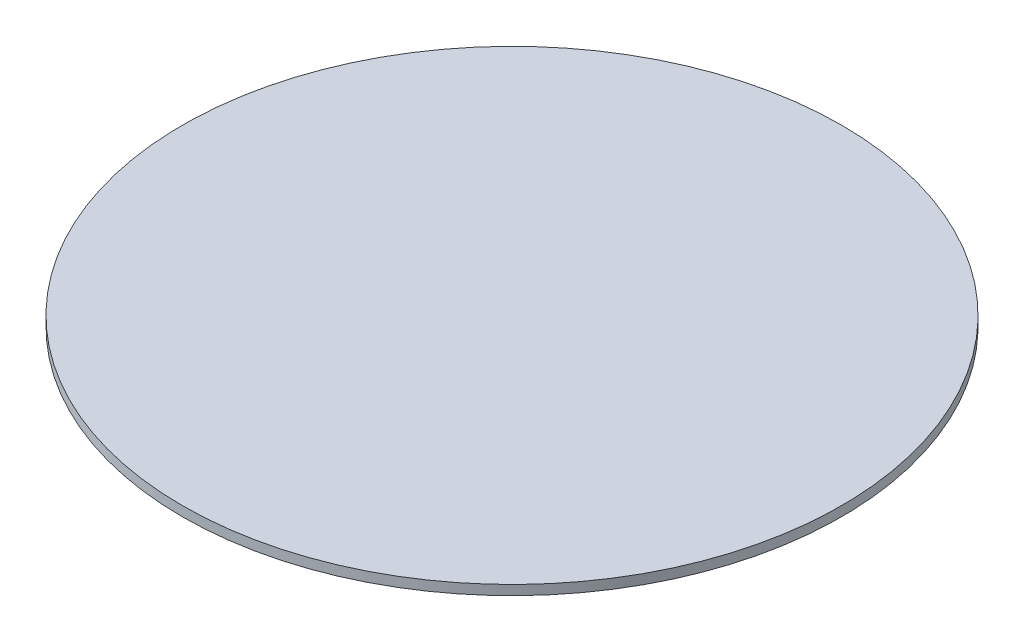
SolidWorks part; units mm, degrees
ref_plane "前视基准面" through (0, 0, 0) normal (0, 0, 1) x (1, 0, 0)
ref_plane "上视基准面" through (0, 0, 0) normal (0, 1, 0) x (1, 0, 0)
ref_plane "右视基准面" through (0, 0, 0) normal (1, 0, 0) x (0, 0, -1)
sketch "草图1" plane through (0, 0, 0) normal (0, 1, 0) x (1, 0, 0)
  circle A0 centre (0, 0) radius 170
  dimension "D1" = 340
extrude "凸台-拉伸1" add sketch "草图1" along normal blind 5
sketch "草图7" plane through (0, 0, 0) normal (0, -1, 0) x (1, 0, 0)
  line L0 (-7, 0) -> (7, 0)
  line L1 (-7, 0) -> (-7, -12)
  line L2 (7, 0) -> (7, 12)
  line L3 (-7, 20.5) -> (-7, -44.5)
  line L4 (7, 44.5) -> (7, -20.5)
  line L6 (-7, 20.5) -> (-72, 20.5)
  line L7 (-7, 20.5) -> (-7, -44.5)
  line L8 (-7, -44.5) -> (-72, -44.5)
  line L9 (-72, 20.5) -> (-72, -44.5)
  line L10 (7, 44.5) -> (72, 44.5)
  line L11 (7, 44.5) -> (7, -20.5)
  line L12 (7, -20.5) -> (72, -20.5)
  line L13 (72, 44.5) -> (72, -20.5)
  circle A0 centre (-72, 20.5) radius 2
  circle A1 centre (-7, 20.5) radius 2
  circle A2 centre (-72, -44.5) radius 2
  circle A3 centre (-7, -44.5) radius 2
  circle A4 centre (7, -20.5) radius 2
  circle A5 centre (72, -20.5) radius 2
  circle A6 centre (7, 44.5) radius 2
  circle A7 centre (72, 44.5) radius 2
  point P4 (0, 0)
  point P9 (-7, -12)
  point P12 (7, 12)
  dimension "D8" = 4
  dimension "D9" = 4
  dimension "D10" = 4
  dimension "D11" = 4
  dimension "D12" = 4
  dimension "D13" = 4
  dimension "D14" = 4
  dimension "D15" = 4
  dimension "D1" = 14
  dimension "D2" = 12
  dimension "D3" = 12
  dimension "D4" = 65
  dimension "D5" = 65
  dimension "D6" = 65
  dimension "D7" = 65
extrude "切除-拉伸3" cut sketch "草图7" against normal blind 3 contours A0 | A2 | A3 | A1 | A4 | A5 | A7 | A6
sketch "草图8" plane through (0, 0, 0) normal (0, -1, 0) x (-1, 0, 0)
  line L0 (-170, 0) -> (170, 0)
  line L1 (0, 170) -> (0, -170)
  circle A0 centre (0, 0) radius 170 construction
  point P7 (0, 0)
  point P10 (0, 0)
sketch "草图9" plane through (0, 0, 0) normal (0, -1, 0) x (1, 0, 0)
  line L0 (-7, 0) -> (7, 0)
  line L1 (-7, 0) -> (-7, 10)
  line L2 (7, 0) -> (7, -10)
  line L3 (7, -32.5) -> (7, 32.5)
  line L4 (-7, 32.5) -> (-7, -32.5)
  line L6 (-7, 32.5) -> (-72, 32.5)
  line L7 (-7, 32.5) -> (-7, -32.5)
  line L8 (-7, -32.5) -> (-72, -32.5)
  line L9 (-72, 32.5) -> (-72, -32.5)
  line L10 (7, 32.5) -> (72, 32.5)
  line L11 (7, 32.5) -> (7, -32.5)
  line L12 (7, -32.5) -> (72, -32.5)
  line L13 (72, 32.5) -> (72, -32.5)
  circle A0 centre (-72, 32.5) radius 2
  circle A1 centre (-72, -32.5) radius 2
  circle A2 centre (72, 32.5) radius 2
  circle A3 centre (72, -32.5) radius 2
  circle A4 centre (-7, 32.5) radius 2
  circle A5 centre (7, 32.5) radius 2
  circle A6 centre (7, -32.5) radius 2
  circle A7 centre (-7, -32.5) radius 2
  point P4 (0, 0)
  point P13 (7, 0)
  point P16 (-7, 0)
  dimension "D2" = 65
  dimension "D3" = 65
  dimension "D5" = 4
  dimension "D7" = 4
  dimension "D10" = 4
  dimension "D11" = 4
  dimension "D12" = 4
  dimension "D13" = 4
  dimension "D4" = 4
  dimension "D6" = 4
  dimension "D1" = 14
  dimension "D8" = 65
  dimension "D9" = 65
extrude "切除-拉伸4" cut sketch "草图9" against normal blind 3 contours A0 | A1 | A4 | A7 | A6 | A5 | A2 | A3
sketch "草图11" plane through (0, 0, 0) normal (0, -1, 0) x (1, 0, 0)
  line L0 (-72, -44.5) -> (-72, -56.5)
  line L1 (-7, -44.5) -> (-7, -56.5)
  line L2 (-72, 20.5) -> (-72, 8.5)
  line L3 (-7, 20.5) -> (-7, 8.5)
  line L4 (7, 32.5) -> (7, 20.5)
  line L5 (7, 20.5) -> (7, 8.5)
  line L6 (72, 32.5) -> (72, 20.5)
  line L7 (72, 20.5) -> (72, 8.5)
  line L8 (7, -32.5) -> (7, -44.5)
  line L9 (7, -44.5) -> (7, -56.5)
  line L10 (-7, 32.5) -> (-7, 44.5)
  line L11 (-7, -32.5) -> (-7, -20.5)
  line L12 (-72, 44.5) -> (-72, 56.5)
  line L13 (-72, -20.5) -> (-72, -8.5)
  line L14 (-72, 8.5) -> (-72, -3.5)
  circle A0 centre (-72, 8.5) radius 2
  circle A1 centre (-7, 8.5) radius 2
  circle A2 centre (-72, -56.5) radius 2
  circle A3 centre (-7, -56.5) radius 2
  circle A4 centre (7, 8.5) radius 2
  circle A5 centre (7, 20.5) radius 2
  circle A6 centre (72, 20.5) radius 2
  circle A7 centre (72, 8.5) radius 2
  circle A8 centre (72, -44.5) radius 2
  circle A9 centre (72, -56.5) radius 2
  circle A10 centre (-72, 44.5) radius 2
  circle A11 centre (-7, 44.5) radius 2
  circle A12 centre (7, -44.5) radius 2
  circle A13 centre (7, -56.5) radius 2
  circle A14 centre (-7, -20.5) radius 2
  circle A15 centre (-72, -20.5) radius 2
  circle A16 centre (-72, 56.5) radius 2
  circle A17 centre (-7, 56.5) radius 2
  circle A18 centre (7, 56.5) radius 2
  circle A19 centre (72, 56.5) radius 2
  circle A21 centre (-72, -8.5) radius 2
  circle A22 centre (-7, -8.5) radius 2
  circle A24 centre (7, -8.5) radius 2
  circle A26 centre (72, -8.5) radius 2
  dimension "D12" = 4
  dimension "D13" = 4
  dimension "D14" = 4
  dimension "D15" = 4
  dimension "D16" = 4
  dimension "D17" = 4
  dimension "D18" = 4
  dimension "D19" = 4
  dimension "D20" = 4
  dimension "D21" = 4
  dimension "D22" = 4
  dimension "D23" = 4
  dimension "D24" = 4
  dimension "D25" = 4
  dimension "D27" = 4
  dimension "D28" = 4
  dimension "D30" = 4
  dimension "D31" = 4
  dimension "D32" = 4
  dimension "D33" = 4
  dimension "D37" = 4
  dimension "D38" = 4
  dimension "D40" = 4
  dimension "D42" = 4
  dimension "D1" = 12
  dimension "D2" = 12
  dimension "D3" = 12
  dimension "D4" = 12
  dimension "D5" = 12
  dimension "D6" = 12
  dimension "D7" = 12
  dimension "D8" = 12
  dimension "D9" = 12
  dimension "D10" = 12
  dimension "D11" = 12
  dimension "D26" = 12
  dimension "D29" = 12
  dimension "D34" = 12
extrude "切除-拉伸5" cut sketch "草图11" against normal blind 3
sketch "草图12" plane through (0, 0, 0) normal (0, -1, 0) x (1, 0, 0)
  line L0 (-7, 56.5) -> (0, 56.5)
  line L1 (-72, 56.5) -> (-65, 56.5)
  line L2 (-72, 56.5) -> (-79, 56.5)
  line L3 (-79, 56.5) -> (-86, 56.5)
  line L4 (-65, 56.5) -> (-58, 56.5)
  line L5 (-7, 56.5) -> (-14, 56.5)
  line L6 (-14, 56.5) -> (-21, 56.5)
  line L7 (7, 56.5) -> (14, 56.5)
  line L8 (14, 56.5) -> (21, 56.5)
  line L9 (72, 56.5) -> (79, 56.5)
  line L10 (79, 56.5) -> (86, 56.5)
  line L11 (72, 56.5) -> (65, 56.5)
  line L12 (65, 56.5) -> (58, 56.5)
  circle A0 centre (0, 56.5) radius 2
  circle A1 centre (-79, 56.5) radius 2
  circle A2 centre (-65, 56.5) radius 2
  circle A3 centre (-86, 56.5) radius 2
  circle A4 centre (-58, 56.5) radius 2
  circle A5 centre (-14, 56.5) radius 2
  circle A6 centre (-21, 56.5) radius 2
  circle A7 centre (14, 56.5) radius 2
  circle A8 centre (21, 56.5) radius 2
  circle A9 centre (86, 56.5) radius 2
  circle A10 centre (79, 56.5) radius 2
  circle A11 centre (65, 56.5) radius 2
  circle A12 centre (58, 56.5) radius 2
  dimension "D2" = 4
  dimension "D5" = 4
  dimension "D6" = 4
  dimension "D8" = 4
  dimension "D10" = 4
  dimension "D13" = 4
  dimension "D14" = 4
  dimension "D17" = 4
  dimension "D18" = 4
  dimension "D23" = 4
  dimension "D24" = 4
  dimension "D25" = 4
  dimension "D26" = 4
  dimension "D1" = 7
  dimension "D3" = 7
  dimension "D4" = 7
  dimension "D7" = 7
  dimension "D9" = 7
  dimension "D11" = 7
  dimension "D12" = 7
  dimension "D15" = 7
  dimension "D16" = 7
  dimension "D19" = 7
  dimension "D20" = 7
  dimension "D21" = 7
  dimension "D22" = 7
extrude "切除-拉伸6" cut sketch "草图12" against normal blind 3 contours A9 | A10 | A11 | A12 | A7 | A8 | A0 | A5 | A6 | A1 | A2 | A4 | A3
pattern_linear "阵列(线性)1" count 5 spacing 12 along (0, 0, -1) of "切除-拉伸6"
sketch "草图13" plane through (0, 0, 0) normal (0, -1, 0) x (1, 0, 0)
  line L0 (-79, -8.5) -> (-72, -8.5)
  line L1 (-86, -8.5) -> (-79, -8.5)
  line L2 (-72, -8.5) -> (-65, -8.5)
  line L3 (-65, -8.5) -> (-58, -8.5)
  line L4 (-7, -8.5) -> (-14, -8.5)
  line L5 (-14, -8.5) -> (-21, -8.5)
  line L6 (72, -8.5) -> (79, -8.5)
  line L7 (79, -8.5) -> (86, -8.5)
  line L8 (72, -8.5) -> (65, -8.5)
  line L9 (65, -8.5) -> (58, -8.5)
  line L10 (-7, -8.5) -> (0, -8.5)
  line L11 (7, -8.5) -> (14, -8.5)
  line L12 (14, -8.5) -> (21, -8.5)
  circle A0 centre (-86, -8.5) radius 2
  circle A1 centre (-79, -8.5) radius 2
  circle A2 centre (-65, -8.5) radius 2
  circle A3 centre (-58, -8.5) radius 2
  circle A4 centre (86, -8.5) radius 2
  circle A5 centre (79, -8.5) radius 2
  circle A6 centre (65, -8.5) radius 2
  circle A7 centre (58, -8.5) radius 2
  circle A8 centre (0, -8.5) radius 2
  circle A9 centre (14, -8.5) radius 2
  circle A10 centre (21, -8.5) radius 2
  circle A11 centre (-14, -8.5) radius 2
  circle A12 centre (-21, -8.5) radius 2
  dimension "D2" = 4
  dimension "D4" = 4
  dimension "D7" = 4
  dimension "D8" = 4
  dimension "D18" = 4
  dimension "D19" = 4
  dimension "D20" = 4
  dimension "D21" = 4
  dimension "D22" = 4
  dimension "D23" = 4
  dimension "D24" = 4
  dimension "D25" = 4
  dimension "D26" = 4
  dimension "D1" = 7
  dimension "D3" = 7
  dimension "D5" = 7
  dimension "D6" = 7
  dimension "D9" = 7
  dimension "D10" = 7
  dimension "D11" = 7
  dimension "D12" = 7
  dimension "D13" = 7
  dimension "D14" = 7
  dimension "D15" = 7
  dimension "D16" = 7
  dimension "D17" = 7
extrude "切除-拉伸7" cut sketch "草图13" against normal blind 3 contours A4 | A5 | A6 | A7 | A8 | A9 | A10 | A11 | A12 | A0 | A1 | A2 | A3
pattern_linear "阵列(线性)3" count 5 spacing 12 along (0, 0, -1) of "切除-拉伸7"
sketch "草图14" plane through (0, 0, 0) normal (0, -1, 0) x (1, 0, 0)
  line L1 (-94.1693, 64.2978) -> (-9.8405, 64.2978)
  line L2 (-94.1693, 64.2978) -> (-94.1693, 51.4067)
  line L3 (-94.1693, 51.4067) -> (-9.8405, 51.4067)
  line L4 (-9.8405, 64.2978) -> (-9.8405, 51.4067)
  line L5 (11.1709, -50.7337) -> (90.0983, -50.7337)
  line L6 (11.1709, -50.7337) -> (11.1709, -63.126)
  line L7 (11.1709, -63.126) -> (90.0983, -63.126)
  line L8 (90.0983, -50.7337) -> (90.0983, -63.126)
extrude "凸台-拉伸2" add sketch "草图14" against normal blind 4
